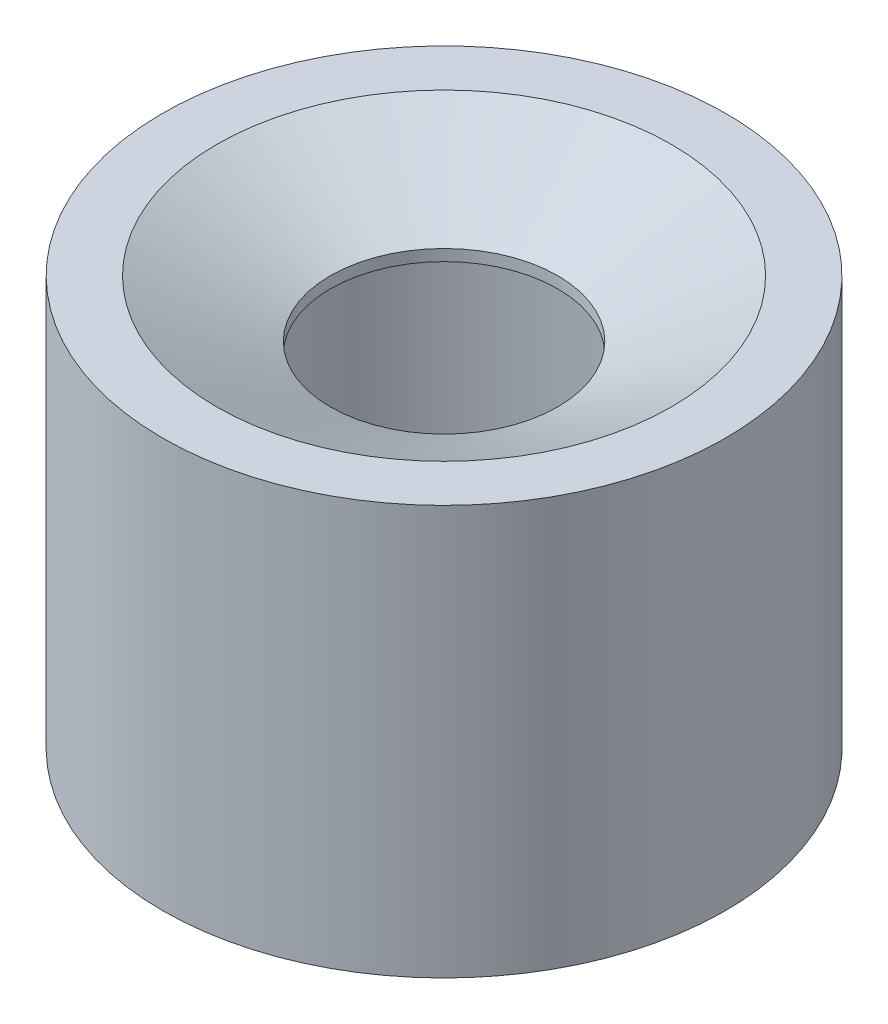
SolidWorks part; units mm, degrees
ref_plane "Front Plane" through (0, 0, 0) normal (0, 0, 1) x (1, 0, 0)
ref_plane "Top Plane" through (0, 0, 0) normal (0, 1, 0) x (1, 0, 0)
ref_plane "Right Plane" through (0, 0, 0) normal (1, 0, 0) x (0, 0, -1)
sketch "Sketch1" plane through (0, 0, 0) normal (0, 1, 0) x (1, 0, 0)
  circle A0 centre (0, 0) radius 1.975
  circle A1 centre (0, 0) radius 2.475
  dimension "D1" = 3.95
  dimension "D2" = 0.5
extrude "Boss-Extrude1" add sketch "Sketch1" along normal blind 3
sketch "Sketch2" plane through (0, 3, 0) normal (0, 1, 0) x (1, 0, 0)
  circle A0 centre (0, 0) radius 2.475
  circle A1 centre (0, 0) radius 1
  dimension "D1" = 2
extrude "Boss-Extrude2" add sketch "Sketch2" along normal blind 0.6
chamfer "Chamfer1" distance 1 distance2 0.5 1 edges at (0, 3.6, 1)
